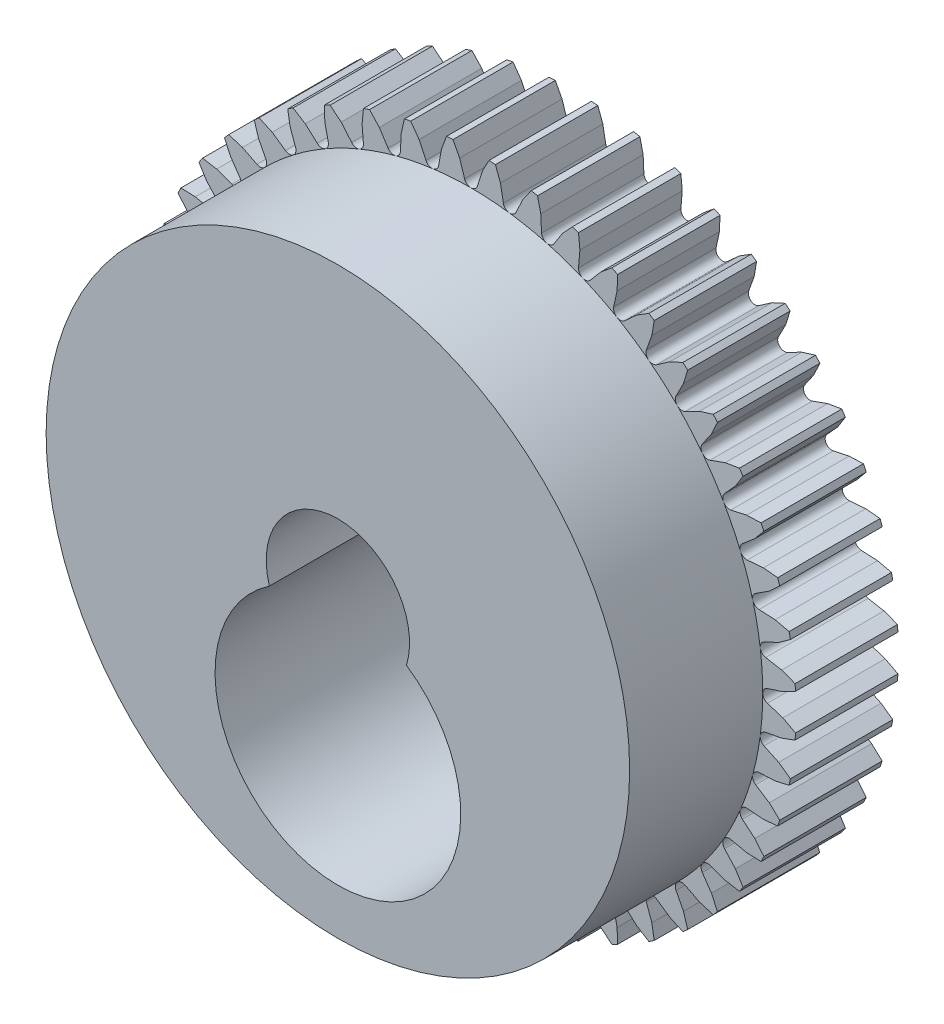
SolidWorks part; units mm, degrees
ref_plane "Front Plane" through (0, 0, 0) normal (0, 0, 1) x (1, 0, 0)
ref_plane "Top Plane" through (0, 0, 0) normal (0, 1, 0) x (1, 0, 0)
ref_plane "Right Plane" through (0, 0, 0) normal (1, 0, 0) x (0, 0, -1)
sketch "Sketch2" plane through (0, 0, 0) normal (0, 0, 1) x (1, 0, 0)
  line L0 (0, -15.875) -> (0, -14.25) construction
  line L1 (15.875, 0) -> (-15.875, 0) construction
  line L2 (-0.8814, 15.8505) -> (-0.5524, 15.23)
  line L3 (-0.5524, 15.23) -> (-0.3111, 14.477)
  line L4 (0.8814, 15.8505) -> (0.5524, 15.23)
  line L5 (0.5524, 15.23) -> (0.3111, 14.477)
  line L6 (1.195, 15.83) -> (1.4403, 15.1718)
  line L7 (1.4403, 15.1718) -> (1.5812, 14.3937)
  line L8 (2.9428, 15.5999) -> (2.5356, 15.0276)
  line L9 (2.5356, 15.0276) -> (2.1981, 14.3125)
  line L10 (3.251, 15.5385) -> (3.4083, 14.854)
  line L11 (3.4083, 14.854) -> (3.4464, 14.0642)
  line L12 (4.9538, 15.0823) -> (4.4754, 14.5681)
  line L13 (4.4754, 14.5681) -> (4.0474, 13.9032)
  line L14 (5.2514, 14.9813) -> (5.3179, 14.2821)
  line L15 (5.3179, 14.2821) -> (5.2527, 13.494)
  line L16 (6.88, 14.3067) -> (6.3386, 13.8593)
  line L17 (6.3386, 13.8593) -> (5.8275, 13.2559)
  line L18 (7.1619, 14.1677) -> (7.1366, 13.4657)
  line L19 (7.1366, 13.4657) -> (6.9691, 12.693)
  line L20 (8.6886, 13.2862) -> (8.0934, 12.9134)
  line L21 (8.0934, 12.9134) -> (7.5079, 12.3819)
  line L22 (8.9499, 13.1116) -> (8.8332, 12.419)
  line L23 (8.8332, 12.419) -> (8.5662, 11.6747)
  line L24 (10.3485, 12.0385) -> (9.7097, 11.7465)
  line L25 (9.7097, 11.7465) -> (9.0598, 11.296)
  line L26 (10.5848, 11.8313) -> (10.3786, 11.1598)
  line L27 (10.3786, 11.1598) -> (10.0168, 10.4567)
  line L28 (11.8313, 10.5848) -> (11.1598, 10.3786)
  line L29 (11.1598, 10.3786) -> (10.4567, 10.0168)
  line L30 (12.0385, 10.3485) -> (11.7465, 9.7097)
  line L31 (11.7465, 9.7097) -> (11.296, 9.0598)
  line L32 (13.1116, 8.9499) -> (12.419, 8.8332)
  line L33 (12.419, 8.8332) -> (11.6747, 8.5662)
  line L34 (13.2862, 8.6886) -> (12.9134, 8.0934)
  line L35 (12.9134, 8.0934) -> (12.3819, 7.5079)
  line L36 (14.1677, 7.1619) -> (13.4657, 7.1366)
  line L37 (13.4657, 7.1366) -> (12.693, 6.9691)
  line L38 (14.3067, 6.88) -> (13.8593, 6.3386)
  line L39 (13.8593, 6.3386) -> (13.2559, 5.8275)
  line L40 (14.9813, 5.2514) -> (14.2821, 5.3179)
  line L41 (14.2821, 5.3179) -> (13.494, 5.2527)
  line L42 (15.0823, 4.9538) -> (14.5681, 4.4754)
  line L43 (14.5681, 4.4754) -> (13.9032, 4.0474)
  line L44 (15.5385, 3.251) -> (14.854, 3.4083)
  line L45 (14.854, 3.4083) -> (14.0642, 3.4464)
  line L46 (15.5999, 2.9428) -> (15.0276, 2.5356)
  line L47 (15.0276, 2.5356) -> (14.3125, 2.1981)
  line L48 (15.83, 1.195) -> (15.1718, 1.4403)
  line L49 (15.1718, 1.4403) -> (14.3937, 1.5812)
  line L50 (15.8505, 0.8814) -> (15.23, 0.5524)
  line L51 (15.23, 0.5524) -> (14.477, 0.3111)
  line L52 (15.8505, -0.8814) -> (15.23, -0.5524)
  line L53 (15.23, -0.5524) -> (14.477, -0.3111)
  line L54 (15.83, -1.195) -> (15.1718, -1.4403)
  line L55 (15.1718, -1.4403) -> (14.3937, -1.5812)
  line L56 (15.5999, -2.9428) -> (15.0276, -2.5356)
  line L57 (15.0276, -2.5356) -> (14.3125, -2.1981)
  line L58 (15.5385, -3.251) -> (14.854, -3.4083)
  line L59 (14.854, -3.4083) -> (14.0642, -3.4464)
  line L60 (15.0823, -4.9538) -> (14.5681, -4.4754)
  line L61 (14.5681, -4.4754) -> (13.9032, -4.0474)
  line L62 (14.9813, -5.2514) -> (14.2821, -5.3179)
  line L63 (14.2821, -5.3179) -> (13.494, -5.2527)
  line L64 (14.3067, -6.88) -> (13.8593, -6.3386)
  line L65 (13.8593, -6.3386) -> (13.2559, -5.8275)
  line L66 (14.1677, -7.1619) -> (13.4657, -7.1366)
  line L67 (13.4657, -7.1366) -> (12.693, -6.9691)
  line L68 (13.2862, -8.6886) -> (12.9134, -8.0934)
  line L69 (12.9134, -8.0934) -> (12.3819, -7.5079)
  line L70 (13.1116, -8.9499) -> (12.419, -8.8332)
  line L71 (12.419, -8.8332) -> (11.6747, -8.5662)
  line L72 (12.0385, -10.3485) -> (11.7465, -9.7097)
  line L73 (11.7465, -9.7097) -> (11.296, -9.0598)
  line L74 (11.8313, -10.5848) -> (11.1598, -10.3786)
  line L75 (11.1598, -10.3786) -> (10.4567, -10.0168)
  line L76 (10.5848, -11.8313) -> (10.3786, -11.1598)
  line L77 (10.3786, -11.1598) -> (10.0168, -10.4567)
  line L78 (10.3485, -12.0385) -> (9.7097, -11.7465)
  line L79 (9.7097, -11.7465) -> (9.0598, -11.296)
  line L80 (8.9499, -13.1116) -> (8.8332, -12.419)
  line L81 (8.8332, -12.419) -> (8.5662, -11.6747)
  line L82 (8.6886, -13.2862) -> (8.0934, -12.9134)
  line L83 (8.0934, -12.9134) -> (7.5079, -12.3819)
  line L84 (7.1619, -14.1677) -> (7.1366, -13.4657)
  line L85 (7.1366, -13.4657) -> (6.9691, -12.693)
  line L86 (6.88, -14.3067) -> (6.3386, -13.8593)
  line L87 (6.3386, -13.8593) -> (5.8275, -13.2559)
  line L88 (5.2514, -14.9813) -> (5.3179, -14.2821)
  line L89 (5.3179, -14.2821) -> (5.2527, -13.494)
  line L90 (4.9538, -15.0823) -> (4.4754, -14.5681)
  line L91 (4.4754, -14.5681) -> (4.0474, -13.9032)
  line L92 (3.251, -15.5385) -> (3.4083, -14.854)
  line L93 (3.4083, -14.854) -> (3.4464, -14.0642)
  line L94 (2.9428, -15.5999) -> (2.5356, -15.0276)
  line L95 (2.5356, -15.0276) -> (2.1981, -14.3125)
  line L96 (1.195, -15.83) -> (1.4403, -15.1718)
  line L97 (1.4403, -15.1718) -> (1.5812, -14.3937)
  line L98 (0.8814, -15.8505) -> (0.5524, -15.23)
  line L99 (0.5524, -15.23) -> (0.3111, -14.477)
  line L100 (-0.8814, -15.8505) -> (-0.5524, -15.23)
  line L101 (-0.5524, -15.23) -> (-0.3111, -14.477)
  line L102 (-1.195, -15.83) -> (-1.4403, -15.1718)
  line L103 (-1.4403, -15.1718) -> (-1.5812, -14.3937)
  line L104 (-2.9428, -15.5999) -> (-2.5356, -15.0276)
  line L105 (-2.5356, -15.0276) -> (-2.1981, -14.3125)
  line L106 (-3.251, -15.5385) -> (-3.4083, -14.854)
  line L107 (-3.4083, -14.854) -> (-3.4464, -14.0642)
  line L108 (-4.9538, -15.0823) -> (-4.4754, -14.5681)
  line L109 (-4.4754, -14.5681) -> (-4.0474, -13.9032)
  line L110 (-5.2514, -14.9813) -> (-5.3179, -14.2821)
  line L111 (-5.3179, -14.2821) -> (-5.2527, -13.494)
  line L112 (-6.88, -14.3067) -> (-6.3386, -13.8593)
  line L113 (-6.3386, -13.8593) -> (-5.8275, -13.2559)
  line L114 (-7.1619, -14.1677) -> (-7.1366, -13.4657)
  line L115 (-7.1366, -13.4657) -> (-6.9691, -12.693)
  line L116 (-8.6886, -13.2862) -> (-8.0934, -12.9134)
  line L117 (-8.0934, -12.9134) -> (-7.5079, -12.3819)
  line L118 (-8.9499, -13.1116) -> (-8.8332, -12.419)
  line L119 (-8.8332, -12.419) -> (-8.5662, -11.6747)
  line L120 (-10.3485, -12.0385) -> (-9.7097, -11.7465)
  line L121 (-9.7097, -11.7465) -> (-9.0598, -11.296)
  line L122 (-10.5848, -11.8313) -> (-10.3786, -11.1598)
  line L123 (-10.3786, -11.1598) -> (-10.0168, -10.4567)
  line L124 (-11.8313, -10.5848) -> (-11.1598, -10.3786)
  line L125 (-11.1598, -10.3786) -> (-10.4567, -10.0168)
  line L126 (-12.0385, -10.3485) -> (-11.7465, -9.7097)
  line L127 (-11.7465, -9.7097) -> (-11.296, -9.0598)
  line L128 (-13.1116, -8.9499) -> (-12.419, -8.8332)
  line L129 (-12.419, -8.8332) -> (-11.6747, -8.5662)
  line L130 (-13.2862, -8.6886) -> (-12.9134, -8.0934)
  line L131 (-12.9134, -8.0934) -> (-12.3819, -7.5079)
  line L132 (-14.1677, -7.1619) -> (-13.4657, -7.1366)
  line L133 (-13.4657, -7.1366) -> (-12.693, -6.9691)
  line L134 (-14.3067, -6.88) -> (-13.8593, -6.3386)
  line L135 (-13.8593, -6.3386) -> (-13.2559, -5.8275)
  line L136 (-14.9813, -5.2514) -> (-14.2821, -5.3179)
  line L137 (-14.2821, -5.3179) -> (-13.494, -5.2527)
  line L138 (-15.0823, -4.9538) -> (-14.5681, -4.4754)
  line L139 (-14.5681, -4.4754) -> (-13.9032, -4.0474)
  line L140 (-15.5385, -3.251) -> (-14.854, -3.4083)
  line L141 (-14.854, -3.4083) -> (-14.0642, -3.4464)
  line L142 (-15.5999, -2.9428) -> (-15.0276, -2.5356)
  line L143 (-15.0276, -2.5356) -> (-14.3125, -2.1981)
  line L144 (-15.83, -1.195) -> (-15.1718, -1.4403)
  line L145 (-15.1718, -1.4403) -> (-14.3937, -1.5812)
  line L146 (-15.8505, -0.8814) -> (-15.23, -0.5524)
  line L147 (-15.23, -0.5524) -> (-14.477, -0.3111)
  line L148 (-15.8505, 0.8814) -> (-15.23, 0.5524)
  line L149 (-15.23, 0.5524) -> (-14.477, 0.3111)
  line L150 (-15.83, 1.195) -> (-15.1718, 1.4403)
  line L151 (-15.1718, 1.4403) -> (-14.3937, 1.5812)
  line L152 (-15.5999, 2.9428) -> (-15.0276, 2.5356)
  line L153 (-15.0276, 2.5356) -> (-14.3125, 2.1981)
  line L154 (-15.5385, 3.251) -> (-14.854, 3.4083)
  line L155 (-14.854, 3.4083) -> (-14.0642, 3.4464)
  line L156 (-15.0823, 4.9538) -> (-14.5681, 4.4754)
  line L157 (-14.5681, 4.4754) -> (-13.9032, 4.0474)
  line L158 (-14.9813, 5.2514) -> (-14.2821, 5.3179)
  line L159 (-14.2821, 5.3179) -> (-13.494, 5.2527)
  line L160 (-14.3067, 6.88) -> (-13.8593, 6.3386)
  line L161 (-13.8593, 6.3386) -> (-13.2559, 5.8275)
  line L162 (-14.1677, 7.1619) -> (-13.4657, 7.1366)
  line L163 (-13.4657, 7.1366) -> (-12.693, 6.9691)
  line L164 (-13.2862, 8.6886) -> (-12.9134, 8.0934)
  line L165 (-12.9134, 8.0934) -> (-12.3819, 7.5079)
  line L166 (-13.1116, 8.9499) -> (-12.419, 8.8332)
  line L167 (-12.419, 8.8332) -> (-11.6747, 8.5662)
  line L168 (-12.0385, 10.3485) -> (-11.7465, 9.7097)
  line L169 (-11.7465, 9.7097) -> (-11.296, 9.0598)
  line L170 (-11.8313, 10.5848) -> (-11.1598, 10.3786)
  line L171 (-11.1598, 10.3786) -> (-10.4567, 10.0168)
  line L172 (-10.5848, 11.8313) -> (-10.3786, 11.1598)
  line L173 (-10.3786, 11.1598) -> (-10.0168, 10.4567)
  line L174 (-10.3485, 12.0385) -> (-9.7097, 11.7465)
  line L175 (-9.7097, 11.7465) -> (-9.0598, 11.296)
  line L176 (-8.9499, 13.1116) -> (-8.8332, 12.419)
  line L177 (-8.8332, 12.419) -> (-8.5662, 11.6747)
  line L178 (-8.6886, 13.2862) -> (-8.0934, 12.9134)
  line L179 (-8.0934, 12.9134) -> (-7.5079, 12.3819)
  line L180 (-7.1619, 14.1677) -> (-7.1366, 13.4657)
  line L181 (-7.1366, 13.4657) -> (-6.9691, 12.693)
  line L182 (-6.88, 14.3067) -> (-6.3386, 13.8593)
  line L183 (-6.3386, 13.8593) -> (-5.8275, 13.2559)
  line L184 (-5.2514, 14.9813) -> (-5.3179, 14.2821)
  line L185 (-5.3179, 14.2821) -> (-5.2527, 13.494)
  line L186 (-4.9538, 15.0823) -> (-4.4754, 14.5681)
  line L187 (-4.4754, 14.5681) -> (-4.0474, 13.9032)
  line L188 (-3.251, 15.5385) -> (-3.4083, 14.854)
  line L189 (-3.4083, 14.854) -> (-3.4464, 14.0642)
  line L190 (-2.9428, 15.5999) -> (-2.5356, 15.0276)
  line L191 (-2.5356, 15.0276) -> (-2.1981, 14.3125)
  line L192 (-1.195, 15.83) -> (-1.4403, 15.1718)
  line L193 (-1.4403, 15.1718) -> (-1.5812, 14.3937)
  line L194 (0, 0) -> (0, 15.875) construction
  circle A1 centre (0, 0) radius 15.875
  arc A2 (-7.1366, 13.4657) -> (-6.3386, 13.8593) centre (0, 0) ccw construction
  arc A3 (-0.3111, 14.477) -> (0.3111, 14.477) centre (0, 14.5767) ccw
  arc A4 (1.5812, 14.3937) -> (2.1981, 14.3125) centre (1.9026, 14.452) ccw
  arc A5 (-7.1366, 13.4657) -> (-6.3386, 13.8593) centre (0, 0) ccw construction
  arc A6 (3.4464, 14.0642) -> (4.0474, 13.9032) centre (3.7727, 14.08) ccw
  arc A7 (-7.1366, 13.4657) -> (-6.3386, 13.8593) centre (0, 0) ccw construction
  arc A8 (5.2527, 13.494) -> (5.8275, 13.2559) centre (5.5782, 13.4671) ccw
  arc A9 (-7.1366, 13.4657) -> (-6.3386, 13.8593) centre (0, 0) ccw construction
  arc A10 (6.9691, 12.693) -> (7.5079, 12.3819) centre (7.2883, 12.6238) ccw
  arc A11 (-7.1366, 13.4657) -> (-6.3386, 13.8593) centre (0, 0) ccw construction
  arc A12 (8.5662, 11.6747) -> (9.0598, 11.296) centre (8.8737, 11.5644) ccw
  arc A13 (-7.1366, 13.4657) -> (-6.3386, 13.8593) centre (0, 0) ccw construction
  arc A14 (10.0168, 10.4567) -> (10.4567, 10.0168) centre (10.3073, 10.3073) ccw
  arc A15 (-7.1366, 13.4657) -> (-6.3386, 13.8593) centre (0, 0) ccw construction
  arc A16 (11.296, 9.0598) -> (11.6747, 8.5662) centre (11.5644, 8.8737) ccw
  arc A17 (-7.1366, 13.4657) -> (-6.3386, 13.8593) centre (0, 0) ccw construction
  arc A18 (12.3819, 7.5079) -> (12.693, 6.9691) centre (12.6238, 7.2883) ccw
  arc A19 (-7.1366, 13.4657) -> (-6.3386, 13.8593) centre (0, 0) ccw construction
  arc A20 (13.2559, 5.8275) -> (13.494, 5.2527) centre (13.4671, 5.5782) ccw
  arc A21 (-7.1366, 13.4657) -> (-6.3386, 13.8593) centre (0, 0) ccw construction
  arc A22 (13.9032, 4.0474) -> (14.0642, 3.4464) centre (14.08, 3.7727) ccw
  arc A23 (-7.1366, 13.4657) -> (-6.3386, 13.8593) centre (0, 0) ccw construction
  arc A24 (14.3125, 2.1981) -> (14.3937, 1.5812) centre (14.452, 1.9026) ccw
  arc A25 (-7.1366, 13.4657) -> (-6.3386, 13.8593) centre (0, 0) ccw construction
  arc A26 (14.477, 0.3111) -> (14.477, -0.3111) centre (14.5767, 0) ccw
  arc A27 (-7.1366, 13.4657) -> (-6.3386, 13.8593) centre (0, 0) ccw construction
  arc A28 (14.3937, -1.5812) -> (14.3125, -2.1981) centre (14.452, -1.9026) ccw
  arc A29 (-7.1366, 13.4657) -> (-6.3386, 13.8593) centre (0, 0) ccw construction
  arc A30 (14.0642, -3.4464) -> (13.9032, -4.0474) centre (14.08, -3.7727) ccw
  arc A31 (-7.1366, 13.4657) -> (-6.3386, 13.8593) centre (0, 0) ccw construction
  arc A32 (13.494, -5.2527) -> (13.2559, -5.8275) centre (13.4671, -5.5782) ccw
  arc A33 (-7.1366, 13.4657) -> (-6.3386, 13.8593) centre (0, 0) ccw construction
  arc A34 (12.693, -6.9691) -> (12.3819, -7.5079) centre (12.6238, -7.2883) ccw
  arc A35 (-7.1366, 13.4657) -> (-6.3386, 13.8593) centre (0, 0) ccw construction
  arc A36 (11.6747, -8.5662) -> (11.296, -9.0598) centre (11.5644, -8.8737) ccw
  arc A37 (-7.1366, 13.4657) -> (-6.3386, 13.8593) centre (0, 0) ccw construction
  arc A38 (10.4567, -10.0168) -> (10.0168, -10.4567) centre (10.3073, -10.3073) ccw
  arc A39 (-7.1366, 13.4657) -> (-6.3386, 13.8593) centre (0, 0) ccw construction
  arc A40 (9.0598, -11.296) -> (8.5662, -11.6747) centre (8.8737, -11.5644) ccw
  arc A41 (-7.1366, 13.4657) -> (-6.3386, 13.8593) centre (0, 0) ccw construction
  arc A42 (7.5079, -12.3819) -> (6.9691, -12.693) centre (7.2883, -12.6238) ccw
  arc A43 (-7.1366, 13.4657) -> (-6.3386, 13.8593) centre (0, 0) ccw construction
  arc A44 (5.8275, -13.2559) -> (5.2527, -13.494) centre (5.5782, -13.4671) ccw
  arc A45 (-7.1366, 13.4657) -> (-6.3386, 13.8593) centre (0, 0) ccw construction
  arc A46 (4.0474, -13.9032) -> (3.4464, -14.0642) centre (3.7727, -14.08) ccw
  arc A47 (-7.1366, 13.4657) -> (-6.3386, 13.8593) centre (0, 0) ccw construction
  arc A48 (2.1981, -14.3125) -> (1.5812, -14.3937) centre (1.9026, -14.452) ccw
  arc A49 (-7.1366, 13.4657) -> (-6.3386, 13.8593) centre (0, 0) ccw construction
  arc A50 (0.3111, -14.477) -> (-0.3111, -14.477) centre (0, -14.5767) ccw
  arc A51 (-7.1366, 13.4657) -> (-6.3386, 13.8593) centre (0, 0) ccw construction
  arc A52 (-1.5812, -14.3937) -> (-2.1981, -14.3125) centre (-1.9026, -14.452) ccw
  arc A53 (-7.1366, 13.4657) -> (-6.3386, 13.8593) centre (0, 0) ccw construction
  arc A54 (-3.4464, -14.0642) -> (-4.0474, -13.9032) centre (-3.7727, -14.08) ccw
  arc A55 (-7.1366, 13.4657) -> (-6.3386, 13.8593) centre (0, 0) ccw construction
  arc A56 (-5.2527, -13.494) -> (-5.8275, -13.2559) centre (-5.5782, -13.4671) ccw
  arc A57 (-7.1366, 13.4657) -> (-6.3386, 13.8593) centre (0, 0) ccw construction
  arc A58 (-6.9691, -12.693) -> (-7.5079, -12.3819) centre (-7.2883, -12.6238) ccw
  arc A59 (-7.1366, 13.4657) -> (-6.3386, 13.8593) centre (0, 0) ccw construction
  arc A60 (-8.5662, -11.6747) -> (-9.0598, -11.296) centre (-8.8737, -11.5644) ccw
  arc A61 (-7.1366, 13.4657) -> (-6.3386, 13.8593) centre (0, 0) ccw construction
  arc A62 (-10.0168, -10.4567) -> (-10.4567, -10.0168) centre (-10.3073, -10.3073) ccw
  arc A63 (-7.1366, 13.4657) -> (-6.3386, 13.8593) centre (0, 0) ccw construction
  arc A64 (-11.296, -9.0598) -> (-11.6747, -8.5662) centre (-11.5644, -8.8737) ccw
  arc A65 (-7.1366, 13.4657) -> (-6.3386, 13.8593) centre (0, 0) ccw construction
  arc A66 (-12.3819, -7.5079) -> (-12.693, -6.9691) centre (-12.6238, -7.2883) ccw
  arc A67 (-7.1366, 13.4657) -> (-6.3386, 13.8593) centre (0, 0) ccw construction
  arc A68 (-13.2559, -5.8275) -> (-13.494, -5.2527) centre (-13.4671, -5.5782) ccw
  arc A69 (-7.1366, 13.4657) -> (-6.3386, 13.8593) centre (0, 0) ccw construction
  arc A70 (-13.9032, -4.0474) -> (-14.0642, -3.4464) centre (-14.08, -3.7727) ccw
  arc A71 (-7.1366, 13.4657) -> (-6.3386, 13.8593) centre (0, 0) ccw construction
  arc A72 (-14.3125, -2.1981) -> (-14.3937, -1.5812) centre (-14.452, -1.9026) ccw
  arc A73 (-7.1366, 13.4657) -> (-6.3386, 13.8593) centre (0, 0) ccw construction
  arc A74 (-14.477, -0.3111) -> (-14.477, 0.3111) centre (-14.5767, 0) ccw
  arc A75 (-7.1366, 13.4657) -> (-6.3386, 13.8593) centre (0, 0) ccw construction
  arc A76 (-14.3937, 1.5812) -> (-14.3125, 2.1981) centre (-14.452, 1.9026) ccw
  arc A77 (-7.1366, 13.4657) -> (-6.3386, 13.8593) centre (0, 0) ccw construction
  arc A78 (-14.0642, 3.4464) -> (-13.9032, 4.0474) centre (-14.08, 3.7727) ccw
  arc A79 (-7.1366, 13.4657) -> (-6.3386, 13.8593) centre (0, 0) ccw construction
  arc A80 (-13.494, 5.2527) -> (-13.2559, 5.8275) centre (-13.4671, 5.5782) ccw
  arc A81 (-7.1366, 13.4657) -> (-6.3386, 13.8593) centre (0, 0) ccw construction
  arc A82 (-12.693, 6.9691) -> (-12.3819, 7.5079) centre (-12.6238, 7.2883) ccw
  arc A83 (-7.1366, 13.4657) -> (-6.3386, 13.8593) centre (0, 0) ccw construction
  arc A84 (-11.6747, 8.5662) -> (-11.296, 9.0598) centre (-11.5644, 8.8737) ccw
  arc A85 (-7.1366, 13.4657) -> (-6.3386, 13.8593) centre (0, 0) ccw construction
  arc A86 (-10.4567, 10.0168) -> (-10.0168, 10.4567) centre (-10.3073, 10.3073) ccw
  arc A87 (-7.1366, 13.4657) -> (-6.3386, 13.8593) centre (0, 0) ccw construction
  arc A88 (-9.0598, 11.296) -> (-8.5662, 11.6747) centre (-8.8737, 11.5644) ccw
  arc A89 (-7.1366, 13.4657) -> (-6.3386, 13.8593) centre (0, 0) ccw construction
  arc A90 (-7.5079, 12.3819) -> (-6.9691, 12.693) centre (-7.2883, 12.6238) ccw
  arc A91 (-7.1366, 13.4657) -> (-6.3386, 13.8593) centre (0, 0) ccw construction
  arc A92 (-5.8275, 13.2559) -> (-5.2527, 13.494) centre (-5.5782, 13.4671) ccw
  arc A93 (-7.1366, 13.4657) -> (-6.3386, 13.8593) centre (0, 0) ccw construction
  arc A94 (-4.0474, 13.9032) -> (-3.4464, 14.0642) centre (-3.7727, 14.08) ccw
  arc A95 (-7.1366, 13.4657) -> (-6.3386, 13.8593) centre (0, 0) ccw construction
  arc A96 (-2.1981, 14.3125) -> (-1.5812, 14.3937) centre (-1.9026, 14.452) ccw
  arc A97 (-7.1366, 13.4657) -> (-6.3386, 13.8593) centre (0, 0) ccw construction
  point P8 (0, 0)
  point P11 (0, 0)
  point P15 (0, 0)
  point P397 (0, 0)
  dimension "D2" = 31.75
  dimension "D3" = 30.48
  dimension "D4" = 48
extrude "Boss-Extrude1" add sketch "Sketch2" along normal blind 5 contours A96 L191 L190 A1 L188 L189 A94 L187 L186 L184 L185 A92 L183 L182 L180 L181 A90 L179 L178 L176 L177 A88 L175 L174 L172 L173 A86 L171 L170 L168 L169 A84 L167 L166 L164 L165 A82 L163 L162 L160 L161 A80 L159 L158
sketch "Sketch3" plane through (0, 0, 5) normal (0, 0, 1) x (1, 0, 0)
  circle A0 centre (0, 0) radius 14.25
  dimension "D1" = 28.5
extrude "Boss-Extrude2" add sketch "Sketch3" along normal blind 11.5 from surface at -5 starting at face at (0, 0, 0)
sketch "Sketch4" plane through (0, 0, 0) normal (0, 0, -1) x (-1, 0, 0)
  arc A0 (3.3478, -1.0208) -> (-3.3478, -1.0208) centre (0, 0) ccw
  arc A1 (-3.3478, -1.0208) -> (3.3478, -1.0208) centre (0, -6) ccw
  point P5 (0, 0)
  dimension "D1" = 7
  dimension "D2" = 12
extrude "Cut-Extrude1" cut sketch "Sketch4" against normal through all
